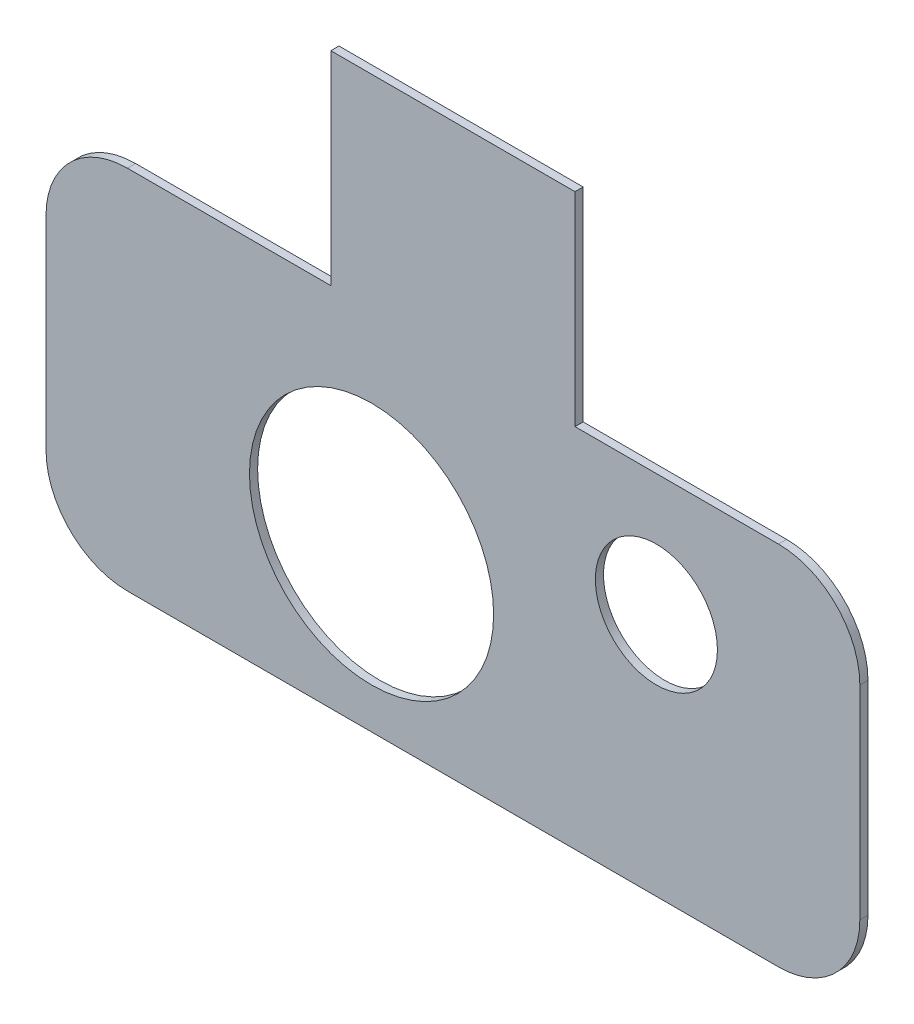
SolidWorks part; units mm, degrees
ref_plane "Front Plane" through (0, 0, 0) normal (0, 0, 1) x (1, 0, 0)
ref_plane "Top Plane" through (0, 0, 0) normal (0, 1, 0) x (1, 0, 0)
ref_plane "Right Plane" through (0, 0, 0) normal (1, 0, 0) x (0, 0, -1)
sketch "Sketch1" plane through (0, 0, 0) normal (0, 0, 1) x (1, 0, 0)
  line L0 (-15.7019, 8.1658) -> (-15.7019, 33.1658)
  line L1 (14.2981, 8.1658) -> (39.2981, 8.1658)
  line L2 (-50.7019, -1.8342) -> (-50.7019, -26.8342)
  line L3 (-40.7019, -36.8342) -> (39.2981, -36.8342)
  line L4 (49.2981, -1.8342) -> (49.2981, -26.8342)
  line L5 (-15.7019, 33.1658) -> (14.2981, 33.1658)
  line L6 (14.2981, 33.1658) -> (14.2981, 8.1658)
  line L7 (-15.7019, 8.1658) -> (-40.7019, 8.1658)
  arc A0 (-50.7019, -26.8342) -> (-40.7019, -36.8342) centre (-40.7019, -26.8342) ccw
  arc A1 (39.2981, -36.8342) -> (49.2981, -26.8342) centre (39.2981, -26.8342) ccw
  arc A2 (39.2981, 8.1658) -> (49.2981, -1.8342) centre (39.2981, -1.8342) cw
  arc A3 (-40.7019, 8.1658) -> (-50.7019, -1.8342) centre (-40.7019, -1.8342) ccw
  circle A4 centre (-10.7019, -16.8342) radius 15
  circle A5 centre (24.2981, -6.8342) radius 7.5
  point P10 (-50.7019, -36.8342)
  point P13 (49.2981, -36.8342)
  point P18 (-50.7019, 8.1658)
  dimension "D6" = 10
  dimension "D7" = 30
  dimension "D8" = 15
  dimension "D1" = 100
  dimension "D2" = 45
  dimension "D3" = 35
  dimension "D4" = 30
  dimension "D5" = 25
  dimension "D9" = 40
  dimension "D10" = 20
  dimension "D11" = 30
  dimension "D12" = 75
extrude "Boss-Extrude1" add sketch "Sketch1" along normal blind 1
